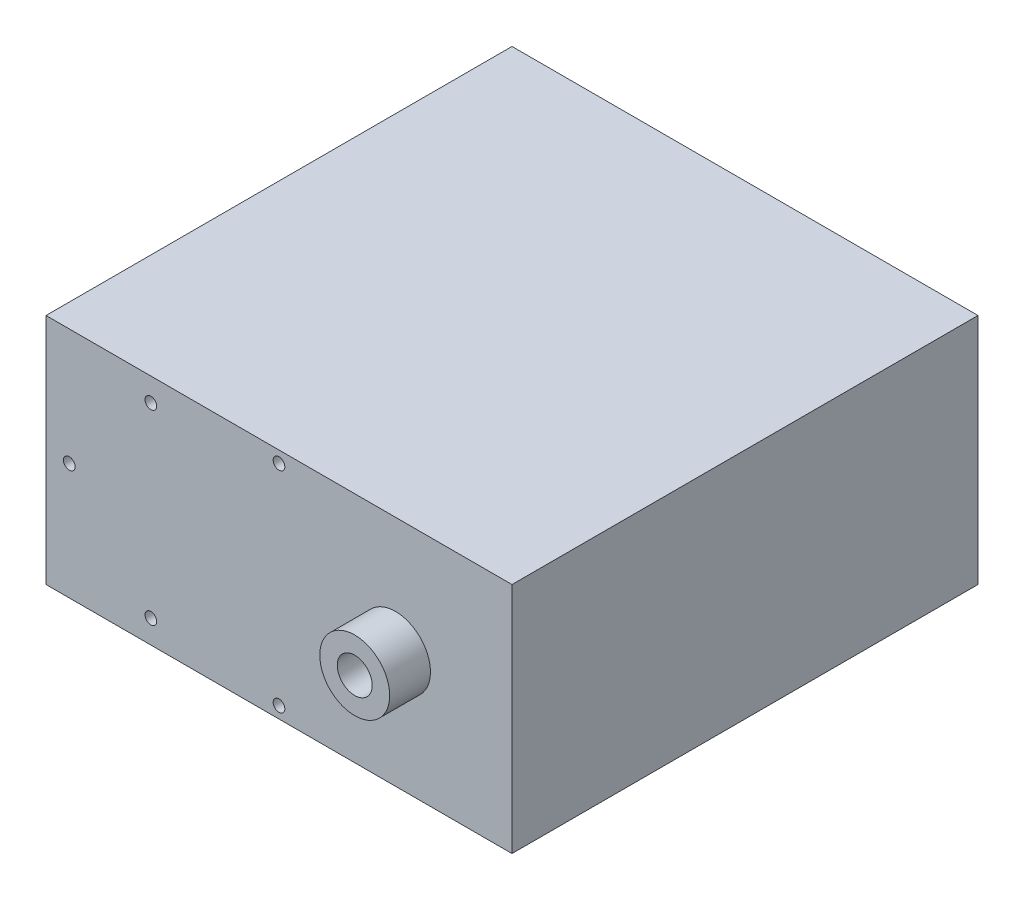
SolidWorks part; units mm, degrees
ref_plane "前视基准面" through (0, 0, 0) normal (0, 0, 1) x (1, 0, 0)
ref_plane "上视基准面" through (0, 0, 0) normal (0, 1, 0) x (1, 0, 0)
ref_plane "右视基准面" through (0, 0, 0) normal (1, 0, 0) x (0, 0, -1)
sketch "草图1" plane through (0, 0, 0) normal (0, 0, 1) x (1, 0, 0)
  line L1 (-20, -10) -> (20, -10)
  line L2 (-20, -10) -> (-20, 10)
  line L3 (-20, 10) -> (20, 10)
  line L4 (20, -10) -> (20, 10)
  line L5 (-20, -10) -> (20, 10) construction
  line L6 (-20, 10) -> (20, -10) construction
  point P0 (0, 0)
  dimension "D1" = 40
  dimension "D2" = 20
extrude "凸台-拉伸1" add sketch "草图1" along normal blind 40
sketch "草图2" plane through (0, 0, 40) normal (0, 0, 1) x (1, 0, 0)
  line L0 (20, -10) -> (20, 10) construction
  circle A0 centre (10, 0) radius 3
  circle A1 centre (10, 0) radius 1.5
  dimension "D1" = 6
  dimension "D2" = 3
  dimension "D3" = 10
extrude "凸台-拉伸2" add sketch "草图2" along normal blind 3.5
sketch "草图3" plane through (0, 0, 0) normal (0, 0, -1) x (-1, 0, 0)
  line L0 (-20, -10) -> (-20, 10) construction
  circle A0 centre (-10, 0) radius 6
  dimension "D1" = 12
  dimension "D2" = 10
extrude "凸台-拉伸3" add sketch "草图3" along normal blind 1
sketch "草图4" plane through (0, 0, -1) normal (0, 0, -1) x (-1, 0, 0)
  circle A0 centre (-10, 0) radius 3
  circle A1 centre (-10, 0) radius 1
  dimension "D1" = 6
  dimension "D2" = 2
extrude "凸台-拉伸4" add sketch "草图4" along normal blind 6
sketch "草图5" plane through (0, 0, 40) normal (0, 0, 1) x (1, 0, 0)
  line L0 (-20, 10) -> (-20, -10) construction
  line L1 (20, 10) -> (-20, 10) construction
  line L2 (-20, -10) -> (20, -10) construction
  circle A0 centre (-18, 0) radius 0.5
  circle A1 centre (-11, 8) radius 0.5
  circle A2 centre (0, 9) radius 0.5
  circle A3 centre (-11, -8) radius 0.5
  circle A4 centre (0, -9) radius 0.5
  dimension "D1" = 1
  dimension "D8" = 1
  dimension "D9" = 1
  dimension "D10" = 1
  dimension "D11" = 1
  dimension "D2" = 2
  dimension "D3" = 9
  dimension "D4" = 2
  dimension "D5" = 20
  dimension "D6" = 1
  dimension "D7" = 9
  dimension "D12" = 2
  dimension "D13" = 1
  dimension "D14" = 20
extrude "切除-拉伸1" cut sketch "草图5" against normal blind 10
sketch "草图6" plane through (0, 0, 0) normal (0, 0, -1) x (-1, 0, 0)
  line L0 (20, 10) -> (20, -10) construction
  line L1 (20, -10) -> (-20, -10) construction
  line L2 (-20, 10) -> (20, 10) construction
  circle A0 centre (18, 0) radius 0.5
  circle A1 centre (11, -8) radius 0.5
  circle A2 centre (0, -9) radius 0.5
  circle A3 centre (11, 8) radius 0.5
  circle A4 centre (0, 9) radius 0.5
  dimension "D1" = 1
  dimension "D2" = 1
  dimension "D3" = 1
  dimension "D4" = 1
  dimension "D5" = 1
  dimension "D6" = 2
  dimension "D7" = 2
  dimension "D8" = 9
  dimension "D9" = 2
  dimension "D10" = 9
  dimension "D11" = 20
  dimension "D12" = 1
  dimension "D13" = 1
  dimension "D14" = 20
extrude "切除-拉伸2" cut sketch "草图6" against normal blind 10
